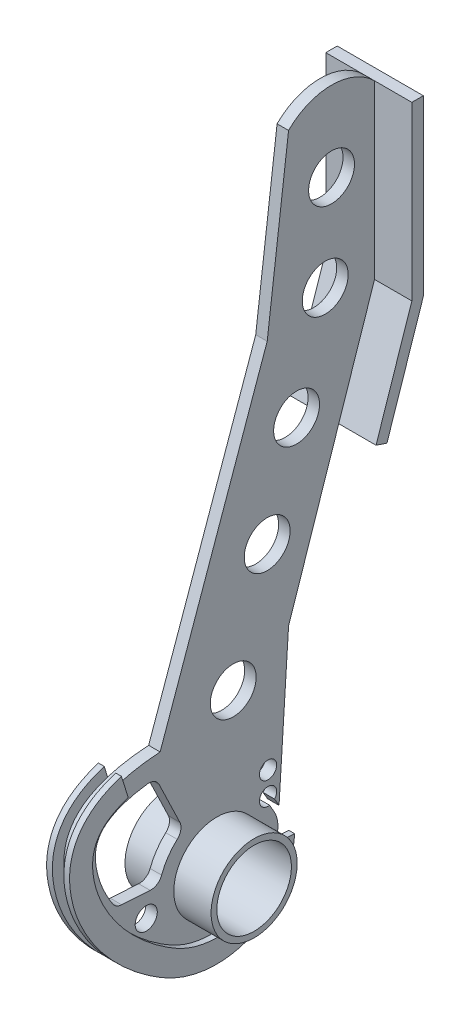
SolidWorks part; units mm, degrees
material "AISI 1020 Steel, Cold Rolled"
ref_plane "Front Plane" through (0, 0, 0) normal (0, 0, 1) x (1, 0, 0)
ref_plane "Top Plane" through (0, 0, 0) normal (0, 1, 0) x (1, 0, 0)
ref_plane "Right Plane" through (0, 0, 0) normal (1, 0, 0) x (0, 0, -1)
sketch "Sketch1" plane through (0, 0, 0) normal (1, 0, 0) x (0, 0, -1)
  line B0 (30.0781, 30.1029) -> (30.0781, 104.8586)
  line B1 (30.0781, 104.8586) -> (43.6562, 145.4782)
  line B2 (43.6562, 145.4782) -> (60.0385, 194.4865)
  line B3 (60.0385, 194.4865) -> (60.0385, 254.4271)
  line B4 (30.0781, 254.4271) -> (22.6293, 194.4865)
  line B5 (22.6293, 194.4865) -> (-14.6833, 89.2308)
  line B6 (30.0781, 30.1029) -> (16.3709, -6.184)
  line B7 (-14.6833, 89.2308) -> (-17.4912, 0.5538)
  circle B8 centre (0, 0) radius 12.7
  arc B9 (-17.4912, 0.5538) -> (16.3709, -6.184) centre (0, 0) ccw
  arc B10 (60.0385, 254.4271) -> (30.0781, 254.4271) centre (45.0583, 239.4469) ccw
  circle B11 centre (45.0583, 232.7881) radius 8
  circle B12 centre (42.8552, 200.5742) radius 8
  circle B13 centre (32.8774, 166.3648) radius 8
  circle B14 centre (22.6293, 133.2845) radius 8
  circle B15 centre (10.7925, 95.0759) radius 8
  circle B16 centre (5.0755, 44.7128) radius 15
sketch_block_instance "Block-break pedal-1"
sketch_block "Block-break pedal" parameters "D1"=35, "D2"=25.4, "D3"=16, "D6"=30, "D4"=40, "D5"=45
extrude "Boss-Extrude1" add sketch "Sketch1" along normal mid plane 4
sketch "Sketch2" plane through (0, 0, 0) normal (1, 0, 0) x (0, 0, -1)
  line L0 (30.0781, 104.8586) -> (60.0385, 194.4865) construction
  line L1 (60.0385, 194.4865) -> (60.0385, 254.4271) construction
  line L2 (47.5636, 157.1672) -> (60.0385, 194.4865)
  line L3 (60.0385, 194.4865) -> (60.0385, 254.4271)
  line L4 (51.3572, 155.899) -> (64.0385, 193.8356)
  line L5 (64.0385, 193.8356) -> (64.0385, 254.4271)
  line L6 (60.0385, 254.4271) -> (64.0385, 254.4271)
  line L7 (47.5636, 157.1672) -> (51.3572, 155.899)
  line L8 (33.8718, 103.5905) -> (64.0385, 193.8356) construction
  line L9 (30.0781, 104.8586) -> (60.0385, 194.4865) construction
  dimension "D2" = 40
  dimension "D1" = 4
extrude "Boss-Extrude2" add sketch "Sketch2" along normal mid plane 30
chamfer "Chamfer1" [suppressed] distance 4 angle 45
sketch "Sketch3" plane through (0, 0, 0) normal (1, 0, 0) x (0, 0, -1)
  circle A0 centre (5.0755, 44.7128) radius 15
  circle A1 centre (5.0755, 44.7128) radius 13
  dimension "D1" = 26
  dimension "D2" = 30
extrude "Boss-Extrude3" add sketch "Sketch3" along normal mid plane 30
sketch "Sketch4" plane through (0, 0, 0) normal (1, 0, 0) x (0, 0, -1)
  line L0 (-14.6833, 89.2308) -> (-17.4912, 0.5538) construction
  line L1 (30.0781, 104.8586) -> (26.1913, 43.3779)
  line L2 (30.0781, 104.8586) -> (36.1617, 104.8586)
  line L3 (36.1617, 104.8586) -> (36.1617, 11.2272)
  line L4 (36.1617, 11.2272) -> (13.6704, -21.7251)
  line L5 (13.6704, -21.7251) -> (-19.282, -21.7251)
  line L6 (-19.282, -21.7251) -> (-29.1541, 7.5043)
  line L7 (-29.1541, 7.5043) -> (-29.1541, 44.7128)
  line L8 (-29.1541, 44.7128) -> (-16.0824, 44.7128)
  arc A0 (-16.0824, 44.7128) -> (26.1913, 43.3779) centre (5.0755, 44.7128) ccw
extrude "Cut-Extrude1" cut sketch "Sketch4" against normal through all both and the other way through all
sketch "Sketch5" plane through (0, 0, 0) normal (1, 0, 0) x (0, 0, -1)
  line L0 (5.0755, 44.7128) -> (-109.9135, 44.7128) construction
  line L1 (5.0755, 44.7128) -> (5.0755, 189.7484) construction
  line L2 (-40.4812, 134.9126) -> (-40.4812, 189.7484)
  line L4 (26.1913, 43.3779) -> (28.5895, 81.3128) construction
  line L5 (30.0781, 104.8586) -> (26.1913, 43.3779) construction
  line L6 (-16.0824, 44.7128) -> (-14.6833, 89.2308)
  arc A0 (-16.0824, 44.7128) -> (26.1913, 43.3779) centre (5.0755, 44.7128) ccw construction
  arc A1 (-16.0824, 44.7128) -> (26.1913, 43.3779) centre (5.0755, 44.7128) ccw
  spline S0 degree 3 poles (-14.6833, 89.2308) (-43.0186, 87.4129) (-49.9313, 59.3702) (-26.5111, 33.2036) (2.5155, 16.7407) (24.9053, 23.0366) (26.1913, 43.3779) knots 0 0 0 0 0.276393 0.582042 0.658224 1 1 1 1
extrude "Boss-Extrude4" add sketch "Sketch5" along normal mid plane 4 contours L6 S0 A1
sketch "Sketch6" plane through (0, 0, 0) normal (1, 0, 0) x (0, 0, -1)
  line L0 (-2.5131, 60.4819) -> (-14.4272, 85.239) construction
  line L1 (5.0755, 44.7128) -> (22.1992, 43.6303) construction
  line L2 (-9.1741, 54.8715) -> (-38.4565, 75.7469) construction
  line L3 (-12.3896, 45.817) -> (-31.6473, 47.0345) construction
  line L4 (-18.1671, 49.1882) -> (-30.059, 49.9401)
  line L5 (-7.809, 64.5683) -> (-16.2419, 82.0917)
  line L6 (-14.9741, 48.9864) -> (-30.059, 49.9401) construction
  line L7 (-6.4216, 61.6853) -> (-16.2419, 82.0917) construction
  line L8 (22.1992, 43.6303) -> (30.9571, 43.0766) construction
  line L9 (30.9571, 43.0766) -> (22.9319, 57.0147) construction
  line L10 (31.8237, 43.5756) -> (25.2098, 55.0625)
  line L11 (30.0904, 42.5776) -> (23.4766, 54.0645)
  line L12 (30.0904, 42.5776) -> (22.0653, 56.5157) construction
  line L13 (31.8237, 43.5756) -> (23.7985, 57.5137) construction
  line L14 (30.0904, 42.5776) -> (31.8237, 43.5756)
  arc A0 (-2.5131, 60.4819) -> (-12.3896, 45.817) centre (5.0755, 44.7128) ccw construction
  arc A1 (-8.7213, 59.8752) -> (-14.1612, 51.7978) centre (5.0755, 44.7128) ccw
  arc A2 (-6.4216, 61.6853) -> (-14.9741, 48.9864) centre (5.0755, 44.7128) ccw construction
  arc A3 (-18.1671, 49.1882) -> (-14.1612, 51.7978) centre (-17.9147, 53.1803) ccw
  arc A4 (-8.7213, 59.8752) -> (-7.809, 64.5683) centre (-11.4133, 62.8337) ccw
  circle A5 centre (-19.5208, 41.4232) radius 3.8523
  arc A6 (25.2098, 55.0625) -> (23.4766, 54.0645) centre (22.9319, 57.0147) ccw
  circle A7 centre (22.9319, 65.0147) radius 3
  spline S0 degree 1 poles (-16.2419, 82.0917) (-30.059, 49.9401) knots 0 0 1 1 construction
  spline S1 degree 3 poles (-16.2419, 82.0917) (-16.7842, 82.0433) (-17.8865, 81.9325) (-19.9357, 81.6777) (-22.3125, 81.2915) (-24.8439, 80.7352) (-27.8169, 79.8893) (-30.7942, 78.6772) (-33.3134, 77.1165) (-34.9838, 75.5593) (-36.0643, 74.0174) (-36.7731, 72.3635) (-37.3205, 69.8215) (-37.2316, 66.6746) (-36.4941, 63.1319) (-35.4127, 59.5602) (-33.8357, 56.0022) (-31.8183, 52.5117) (-30.6592, 50.7803) (-30.059, 49.9401) knots 0.007259 0.007259 0.007259 0.007259 0.01346 0.019661 0.032063 0.044465 0.056866 0.08167 0.106473 0.131277 0.156081 0.180884 0.205688 0.255295 0.280098 0.304902 0.354509 0.379312 0.404116 0.404116 0.404116 0.404116
  spline S2 degree 3 poles (2505.3847, -1525.8992) (555.5798, -27.9825) (63.7889, 100.3157) (-25.0413, 83.8107) (-27.1364, 83.2504) (-30.7491, 81.9688) (-32.2661, 81.2483) (-34.8022, 79.7144) (-35.8218, 78.9026) (-37.4803, 77.224) (-38.1215, 76.357) (-39.1341, 74.5438) (-39.5057, 73.5951) (-40.0267, 71.5822) (-40.1745, 70.5176) (-40.2612, 68.283) (-40.1995, 67.1139) (-39.9677, 65.314) (-39.8674, 64.7065) (-39.6249, 63.4825) (-39.4826, 62.865) (-39.0025, 61.0179) (-38.6102, 59.7923) (-37.2308, 56.1418) (-36.0405, 53.7431) (-33.206, 49.0773) (-31.5621, 46.8107) (-27.9242, 42.4753) (-25.9303, 40.4066) (-21.7051, 36.5291) (-19.4739, 34.7202) (-16.6102, 32.6575) (-16.0337, 32.2548) (-14.8753, 31.4702) (-14.2943, 31.0885) (-12.5581, 29.9896) (-11.4047, 29.3156) (-9.0954, 28.1131) (-7.9398, 27.5846) (-6.1939, 26.9176) (-5.6067, 26.7152) (-4.4195, 26.3492) (-3.8205, 26.1858) (-0.8093, 25.4699) (1.6508, 25.222) (6.3949, 25.4075) (8.6763, 25.8402) (11.7877, 26.9894) (12.7737, 27.4554) (14.6256, 28.5536) (15.4917, 29.1855) (17.0932, 30.6246) (17.829, 31.4318) (19.1591, 33.2453) (19.7536, 34.252) (20.7785, 36.498) (21.2087, 37.7378) (35.9015, 98.9466) (-142.4401, 409.9684) (-2398.1487, 1802.6469) knots -1.088807 -1.088807 -1.088807 -1.088807 0.03125 0.03125 0.0625 0.0625 0.09375 0.09375 0.125 0.125 0.15625 0.15625 0.1875 0.1875 0.21875 0.21875 0.25 0.25 0.265625 0.265625 0.28125 0.28125 0.3125 0.3125 0.375 0.375 0.4375 0.4375 0.5 0.5 0.5625 0.5625 0.578125 0.578125 0.59375 0.59375 0.625 0.625 0.65625 0.65625 0.671875 0.671875 0.6875 0.6875 0.75 0.75 0.8125 0.8125 0.84375 0.84375 0.875 0.875 0.90625 0.90625 0.9375 0.9375 0.96875 0.96875 2.332021 2.332021 2.332021 2.332021 only from (-14.4272, 85.239) to (22.1992, 43.6303)
  spline S3 degree 3 poles (-14.4272, 85.239) (-17.4923, 85.0424) (-20.219, 84.7067) (-25.0413, 83.8107) (-27.1364, 83.2504) (-30.7491, 81.9688) (-32.2661, 81.2483) (-34.8022, 79.7144) (-35.8218, 78.9026) (-37.4803, 77.224) (-38.1215, 76.357) (-39.1341, 74.5438) (-39.5057, 73.5951) (-40.0267, 71.5822) (-40.1745, 70.5176) (-40.2612, 68.283) (-40.1995, 67.1139) (-39.9677, 65.314) (-39.8674, 64.7065) (-39.6249, 63.4825) (-39.4826, 62.865) (-39.0025, 61.0179) (-38.6102, 59.7923) (-37.2308, 56.1418) (-36.0405, 53.7431) (-33.7191, 49.9218) (-32.7226, 48.4604) (-31.6473, 47.0345) knots 0 0 0 0 0.03125 0.03125 0.0625 0.0625 0.09375 0.09375 0.125 0.125 0.15625 0.15625 0.1875 0.1875 0.21875 0.21875 0.25 0.25 0.265625 0.265625 0.28125 0.28125 0.3125 0.3125 0.375 0.375 0.414875 0.414875 0.414875 0.414875 construction
  dimension "D2" = 35
  dimension "D4" = 4
  dimension "D5" = 6
  dimension "D8" = 6
  dimension "D9" = 8
  dimension "D1" = 4
  dimension "D3" = 3
  dimension "D6" = 1
  dimension "D7" = 1
extrude "Cut-Extrude2" cut sketch "Sketch6" against normal through all both and the other way through all
fillet "Fillet1" radius 4 2 edges at (0, 82.0917, 16.2419) (0, 49.9401, 30.059)
sketch "Sketch7" plane through (2, 0, 0) normal (1, 0, 0) x (0, 0, -1)
  line L0 (22.1992, 43.6303) -> (30.1833, 43.1255)
  line L1 (-27.7819, 82.9975) -> (-30.1823, 90.6289)
  spline S0 degree 3 poles (1801.5873, -743.0634) (48.0996, 188.4968) (-82.7175, 96.0012) (-26.5111, 33.2036) (52.6746, -11.7076) (209.2112, 202.1695) (-1661.0545, 1103.1951) knots -0.921457 -0.921457 -0.921457 -0.921457 0.276393 0.582042 0.658224 2.25042 2.25042 2.25042 2.25042 only from (-14.6833, 89.2308) to (26.1913, 43.3779) construction
  spline S1 degree 3 poles (-14.6833, 89.2308) (-43.0186, 87.4129) (-49.9313, 59.3702) (-26.5111, 33.2036) (2.5155, 16.7407) (24.9053, 23.0366) (26.1913, 43.3779) knots 0 0 0 0 0.276393 0.582042 0.658224 1 1 1 1 construction
  spline S2 degree 1 poles (-14.9394, 93.2226) (30.1833, 43.1255) knots 0 0 1 1 construction
  spline S3 degree 3 poles (-14.9394, 93.2226) (-15.757, 93.1701) (-17.4165, 93.0418) (-20.5233, 92.7131) (-24.1608, 92.1604) (-27.2354, 91.4746) (-29.4959, 90.8482) (-30.7757, 90.4456) (-33.7953, 89.3865) (-37.9689, 87.4137) (-42.5756, 83.8071) (-45.8467, 79.4219) (-47.713, 74.6102) (-48.3668, 69.698) (-48.0905, 64.8613) (-47.1478, 60.2094) (-45.2306, 54.2261) (-41.6947, 47.133) (-36.0461, 39.3629) (-29.3494, 32.419) (-23.1562, 27.406) (-18.0251, 23.9215) (-13.992, 21.5546) (-9.6766, 19.5724) (-3.5568, 17.6843) (4.3654, 16.8726) (12.1379, 18.302) (17.8459, 20.9876) (21.7319, 23.8164) (25.0637, 27.4742) (27.2465, 31.1877) (28.5761, 34.5292) (29.3548, 37.2127) (29.8145, 39.5959) (30.0647, 41.5811) (30.1509, 42.6133) (30.1833, 43.1255) knots 0 0 0 0 0.007812 0.015625 0.03125 0.046875 0.052115 0.059928 0.063834 0.09375 0.125 0.15625 0.1875 0.21875 0.25 0.28125 0.3125 0.375 0.4375 0.5 0.5625 0.59375 0.625 0.65625 0.6875 0.75 0.8125 0.84375 0.875 0.90625 0.9375 0.953125 0.96875 0.984375 0.992188 1 1 1 1 only from (-30.1823, 90.6289) to (30.1833, 43.1255)
  spline S4 degree 1 poles (-14.4272, 85.239) (22.1992, 43.6303) knots 0 0 1 1 construction
  spline S5 degree 3 poles (-14.4272, 85.239) (-15.1732, 85.1911) (-16.6932, 85.0736) (-18.7919, 84.8512) (-20.783, 84.5807) (-23.272, 84.1608) (-26.0892, 83.5307) (-29.0148, 82.6296) (-31.5081, 81.6085) (-34.2923, 80.1208) (-36.8404, 78.0905) (-38.7621, 75.4911) (-39.8781, 72.6472) (-40.3227, 69.452) (-40.1381, 65.9465) (-39.3949, 62.2458) (-37.8258, 57.3398) (-34.8501, 51.3445) (-29.9183, 44.5443) (-23.9353, 38.3363) (-18.3613, 33.8208) (-13.7114, 30.6653) (-10.2489, 28.6404) (-6.7932, 27.0593) (-2.047, 25.5966) (4.1151, 24.9733) (9.8162, 26.0571) (13.7596, 27.9216) (16.3576, 29.8174) (18.5646, 32.2389) (20.051, 34.7552) (20.9934, 37.118) (21.5633, 39.0758) (21.9117, 40.8755) (22.1055, 42.4101) (22.1738, 43.2271) (22.1992, 43.6303) knots 0 0 0 0 0.007812 0.015625 0.023438 0.03125 0.046875 0.0625 0.078125 0.09375 0.125 0.15625 0.1875 0.21875 0.25 0.28125 0.3125 0.375 0.4375 0.5 0.5625 0.59375 0.625 0.65625 0.6875 0.75 0.8125 0.84375 0.875 0.90625 0.9375 0.953125 0.96875 0.984375 0.992188 1 1 1 1 only from (-27.7819, 82.9975) to (22.1992, 43.6303)
  dimension "D1" = 4
  dimension "D2" = 4
extrude "Boss-Extrude5" add sketch "Sketch7" along normal blind 2
mirror "Mirror1" about plane through (0, 0, 0) normal (1, 0, 0) of "Boss-Extrude5"
chamfer "Chamfer2" [suppressed] distance 2 angle 45
fillet "Fillet2" radius 10 1 edges at (0, 48.7589, -26.5315)
